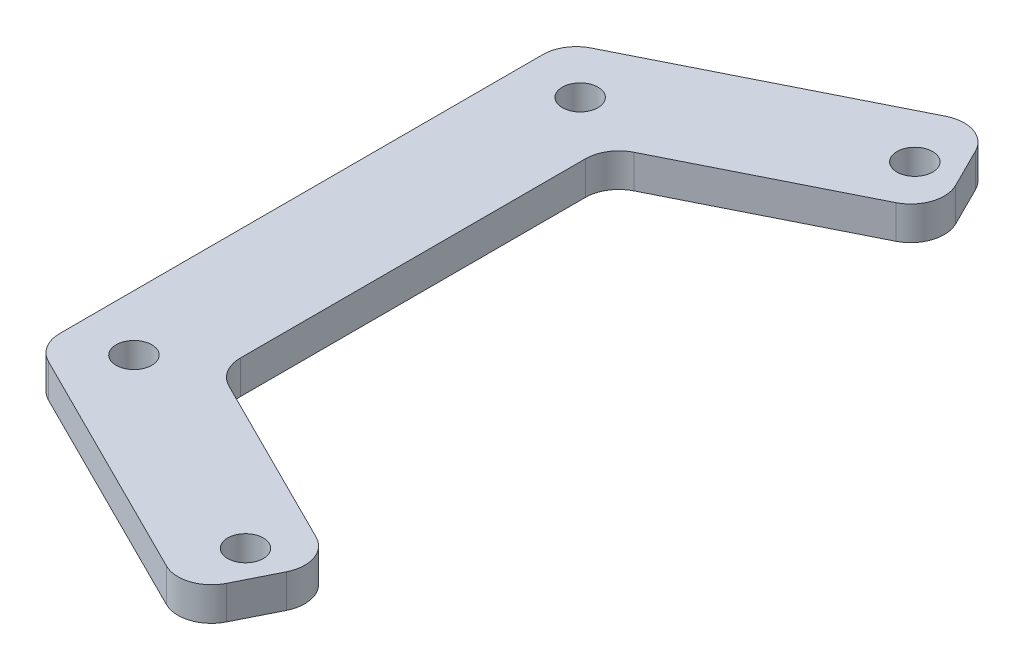
SolidWorks part; units mm, degrees
ref_plane "Alzado" through (0, 0, 0) normal (0, 0, 1) x (1, 0, 0)
ref_plane "Planta" through (0, 0, 0) normal (0, 1, 0) x (1, 0, 0)
ref_plane "Vista lateral" through (0, 0, 0) normal (1, 0, 0) x (0, 0, -1)
sketch "Croquis1" plane through (0, 0, 0) normal (0, 1, 0) x (1, 0, 0)
  line L0 (0, 20) -> (0, -20) construction
  line L1 (-5, 23.5) -> (5, 23.5) construction
  line L2 (-5, 23.5) -> (-5, -23.5)
  line L3 (-5, -23.5) -> (5, -23.5) construction
  line L4 (5, 23.5) -> (5, -23.5) construction
  line L5 (-5, 23.5) -> (5, -23.5) construction
  line L6 (-5, -23.5) -> (5, 23.5) construction
  line L7 (-5, 23.5) -> (20.5279, 36.2639)
  line L8 (5, 17.3197) -> (25, 27.3197)
  line L9 (0, 20) -> (20, 30) construction
  line L10 (25, 27.3197) -> (20.5279, 36.2639)
  line L11 (-5, -23.5) -> (20.5279, -36.2639)
  line L12 (0, -20) -> (20, -30) construction
  line L13 (20.5279, -36.2639) -> (25, -27.3197)
  line L14 (25, -27.3197) -> (5, -17.3197)
  line L15 (5, -17.3197) -> (5, 17.3197)
  circle A0 centre (0, 20) radius 1.6
  circle A1 centre (0, -20) radius 1.6
  circle A2 centre (20, 30) radius 1.6
  circle A3 centre (20, -30) radius 1.6
  point P0 (0, 0)
  point P5 (0, 0)
  point P20 (25.7588, 30)
  point P21 (0, 0)
  point P22 (3.5, 19.1738)
  point P23 (26.229, 30)
  point P25 (0, 0)
  point P26 (0, 0)
  point P27 (0, 0)
  dimension "D4" = 40
  dimension "D3" = 3.2
  dimension "D1" = 10
  dimension "D2" = 47
  dimension "D5" = 20
  dimension "D6" = 10
  dimension "D7" = 10
  dimension "D8" = 10
  dimension "D9" = 30
extrude "Saliente-Extruir1" add sketch "Croquis1" along normal blind 3
fillet "Redondeo1" radius 3 8 edges at (-5, 1.5, -23.5) (-5, 1.5, 23.5) (20.5279, 1.5, 36.2639) (5, 1.5, 17.3197) (25, 1.5, 27.3197) (20.5279, 1.5, -36.2639) (25, 1.5, -27.3197) (5, 1.5, -17.3197)
